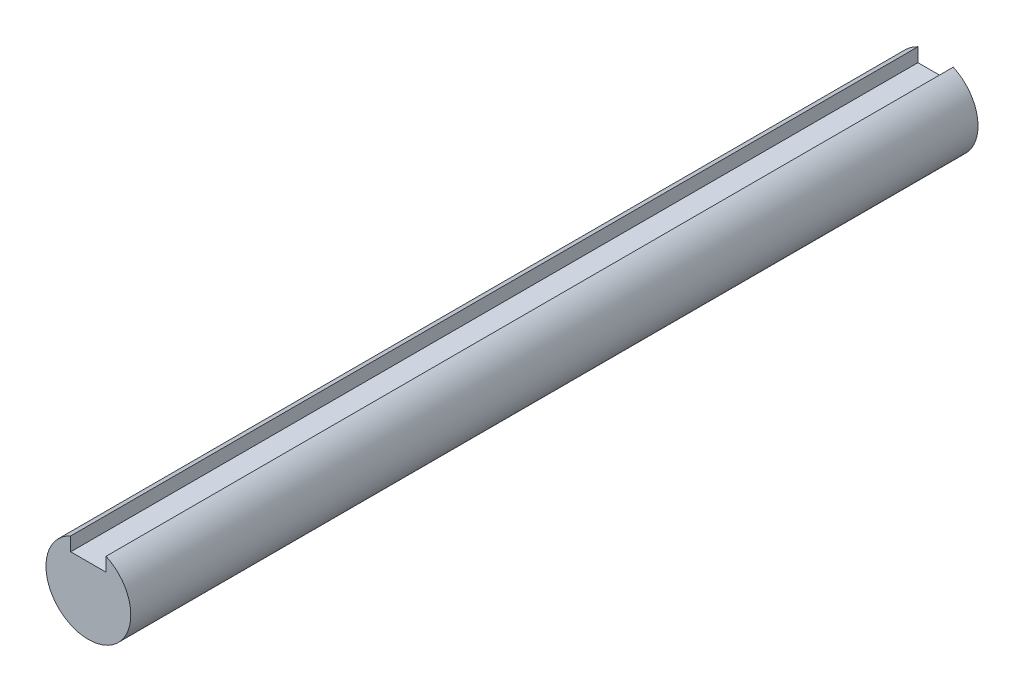
SolidWorks part; units mm, degrees
ref_plane "Alzado" through (0, 0, 0) normal (0, 0, 1) x (1, 0, 0)
ref_plane "Planta" through (0, 0, 0) normal (0, 1, 0) x (1, 0, 0)
ref_plane "Vista lateral" through (0, 0, 0) normal (1, 0, 0) x (0, 0, -1)
sketch "Sketch1" plane through (0, 0, 0) normal (0, 0, 1) x (1, 0, 0)
  line L0 (-2.5, 8.5) -> (-2.5, 5.4544) construction
  line L1 (-2.5, 8.5) -> (2.5, 8.5) construction
  line L2 (-2.5, 5.4544) -> (-2.5, 3.5)
  line L3 (-2.5, 3.5) -> (2.5, 3.5)
  line L4 (2.5, 5.4544) -> (2.5, 3.5)
  line L5 (0, 6) -> (2.5, 3.5) construction
  line L6 (0, 6) -> (2.5, 8.5) construction
  line L7 (-2.5, 8.5) -> (0, 6) construction
  line L8 (2.5, 8.5) -> (2.5, 5.4544) construction
  line L9 (-2.5, 3.5) -> (0, 6) construction
  arc A0 (-2.5, 5.4544) -> (2.5, 5.4544) centre (0, 0) ccw
  arc A1 (2.5, 5.4544) -> (0, 6) centre (0, 0) ccw construction
  arc A2 (0, 6) -> (-2.5, 5.4544) centre (0, 0) ccw construction
  point P3 (0, 6)
  dimension "D1" = 12
  dimension "D2" = 5
  dimension "D3" = 5
extrude "Boss-Extrude1" [suppressed] add sketch "Sketch1" along normal mid plane 100.076
sketch "Sketch2" plane through (0, 0, 0) normal (0, 0, 1) x (1, 0, 0)
  line L1 (-2.5, 8.5) -> (2.5, 8.5)
  line L2 (-2.5, 8.5) -> (-2.5, 3.5)
  line L3 (-2.5, 3.5) -> (2.5, 3.5)
  line L4 (2.5, 8.5) -> (2.5, 3.5)
  line L5 (-2.5, 8.5) -> (2.5, 3.5) construction
  line L6 (-2.5, 3.5) -> (2.5, 8.5) construction
  circle A0 centre (0, 0) radius 6
  point P3 (0, 6)
  dimension "D1" = 12
  dimension "D2" = 5
extrude "Boss-Extrude2" add sketch "Sketch2" along normal mid plane 119.888 contours L2 A0 L4 L3
